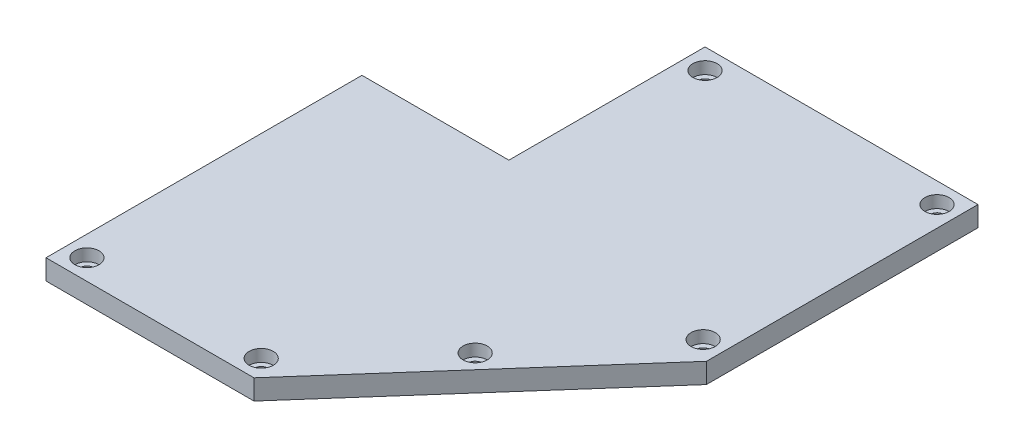
SolidWorks part; units mm, degrees
ref_plane "Front Plane" through (0, 0, 0) normal (0, 0, 1) x (1, 0, 0)
ref_plane "Top Plane" through (0, 0, 0) normal (0, 1, 0) x (1, 0, 0)
ref_plane "Right Plane" through (0, 0, 0) normal (1, 0, 0) x (0, 0, -1)
sketch "Sketch1" plane through (0, 0, 0) normal (0, 1, 0) x (1, 0, 0)
  line L0 (0, 0) -> (-67.7, 0)
  line L1 (-67.7, 0) -> (-67.7, -48.64)
  line L2 (-67.7, -48.64) -> (-104.14, -48.64)
  line L5 (0, 0) -> (0, -67.34)
  line L6 (0, -67.34) -> (-52.5601, -126.9997)
  line L7 (-52.5601, -126.9997) -> (-104.1401, -126.9997)
  line L11 (-104.14, -48.64) -> (-104.1401, -126.9997)
  dimension "D1" = 67.7
  dimension "D2" = 48.64
  dimension "D3" = 36.44
  dimension "D6" = 67.34
  dimension "D7" = 79.51
  dimension "D8" = 138.62
  dimension "D9" = 51.58
extrude "Boss-Extrude1" add sketch "Sketch1" along normal blind 5
sketch "Sketch2" plane through (0, 5, 0) normal (0, 1, 0) x (1, 0, 0)
  line L0 (0, 0) -> (-67.7, 0) construction
  line L1 (0, -67.34) -> (0, 0) construction
  line L2 (-67.7, 0) -> (-67.7, -48.64) construction
  line L3 (-52.5601, -126.9997) -> (0, -67.34) construction
  line L5 (-104.1401, -126.9997) -> (-52.5601, -126.9997) construction
  line L6 (-104.14, -48.64) -> (-104.1401, -126.9997) construction
  point P0 (-5.08, -5.08)
  point P1 (-62.62, -5.08)
  point P8 (-5.08, -63.08)
  point P9 (-30.4665, -94.237)
  point P14 (-99.0601, -121.9197)
  point P17 (-55.8501, -121.9197)
  dimension "D1" = 5.08
  dimension "D2" = 5.08
  dimension "D3" = 5.08
  dimension "D4" = 5.08
  dimension "D5" = 58
  dimension "D6" = 5.08
  dimension "D7" = 5.08
  dimension "D8" = 40.19
  dimension "D9" = 5.08
  dimension "D10" = 5.08
  dimension "D11" = 43.21
  dimension "D12" = 5.08
hole_wizard "Ø4.0mm Dowel Hole1" positions "3DSketch1" profile "Sketch3" hole size "Ø4.0" standard "ANSI Metric"
sketch3d "3DSketch1"
  point P3 (-99.0601, 5, 121.9197)
  point P6 (-55.8501, 5, 121.9197)
  point P9 (-5.08, 5, 63.08)
  point P12 (-30.4665, 5, 94.237)
  point P15 (-5.08, 5, 5.08)
  point P18 (-62.62, 5, 5.08)
sketch "Sketch3" plane through (-99.0601, 5, 121.9197) normal (1, 0, 0) x (0, 0, 1)
  line L0 (0, 0) -> (0, 5)
  line L1 (0, 5) -> (1.75, 5)
  line L2 (1.75, 5) -> (1.75, 0)
  line L5 (1.75, 0) -> (0, 0)
  line L10 (0, 5) -> (-1.75, 5) construction
  line L11 (0, -6.35) -> (0, 107.95) construction
  dimension "Hole Dia." = 3.5
  dimension "Hole Depth" = 5
  dimension "Drill Angle" = 180
sketch "Sketch4" plane through (0, 5, 0) normal (0, 1, 0) x (1, 0, 0)
  circle A0 centre (-99.0601, -121.9197) radius 3
  circle A1 centre (-55.8501, -121.9197) radius 3
  circle A2 centre (-30.4665, -94.237) radius 3
  circle A3 centre (-5.08, -63.08) radius 3
  circle A4 centre (-5.08, -5.08) radius 3
  circle A5 centre (-62.62, -5.08) radius 3
extrude "Cut-Extrude1" cut sketch "Sketch4" against normal blind 3
